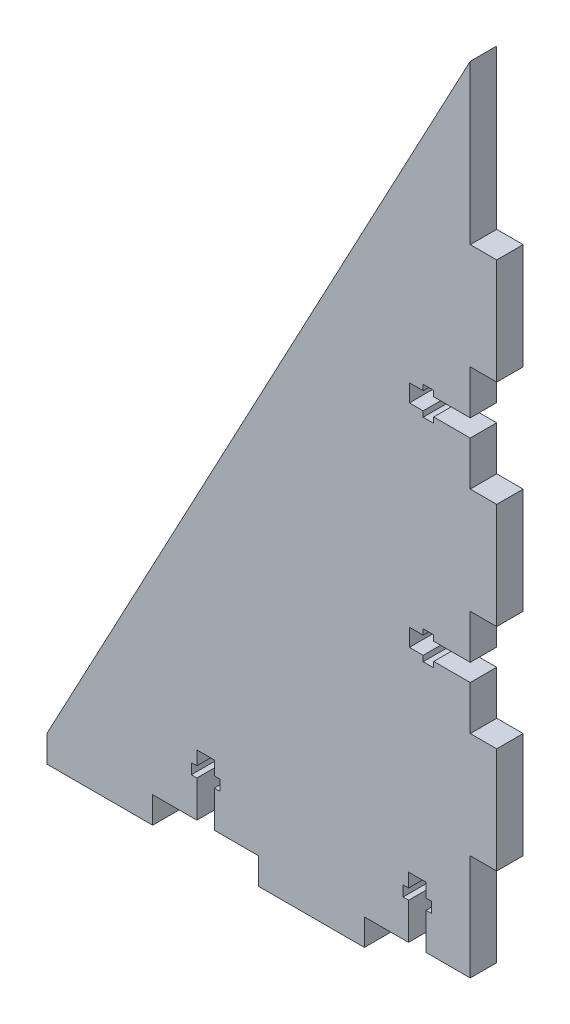
SolidWorks part; units mm, degrees
ref_plane "Front Plane" through (0, 0, 0) normal (0, 0, 1) x (1, 0, 0)
ref_plane "Top Plane" through (0, 0, 0) normal (0, 1, 0) x (1, 0, 0)
ref_plane "Right Plane" through (0, 0, 0) normal (1, 0, 0) x (0, 0, -1)
sketch "Sketch1" plane through (0, 0, 0) normal (0, 0, 1) x (1, 0, 0)
  line L0 (49.1901, 285.75) -> (49.1901, 95.25)
  line L1 (49.1901, 340.0125) -> (49.1901, 289.2125) construction
  line L2 (49.1901, 95.25) -> (-52.4099, 95.25)
  line L3 (-52.4099, 95.25) -> (49.1901, 285.75)
  dimension "D1" = 101.6
  dimension "D2" = 190.5
extrude "Boss-Extrude1" add sketch "Sketch1" along normal mid plane 6.35
sketch "Sketch2" plane through (49.1901, 0, 0) normal (1, 0, 0) x (0, 0, -1)
  line L0 (3.175, 95.25) -> (3.175, 285.75) construction
  line L1 (3.175, 120.65) -> (-3.175, 120.65)
  line L2 (3.175, 120.65) -> (3.175, 146.05)
  line L3 (3.175, 146.05) -> (-3.175, 146.05)
  line L4 (-3.175, 120.65) -> (-3.175, 146.05)
  line L5 (-3.175, 95.25) -> (-3.175, 285.75) construction
  dimension "D1" = 25.4
  dimension "D2" = 25.4
extrude "Boss-Extrude2" add sketch "Sketch2" along normal blind 6.35
pattern_linear "LPattern1" count 3 spacing 50.8 along (0, 1, 0) of "Boss-Extrude2"
sketch "Sketch3" plane through (0, 95.25, 0) normal (0, -1, 0) x (1, 0, 0)
  line L0 (-52.4099, 3.175) -> (49.1901, 3.175) construction
  line L1 (23.7901, 3.175) -> (-1.6099, 3.175)
  line L2 (23.7901, 3.175) -> (23.7901, -3.175)
  line L3 (23.7901, -3.175) -> (-1.6099, -3.175)
  line L4 (-1.6099, 3.175) -> (-1.6099, -3.175)
  line L5 (-52.4099, -3.175) -> (49.1901, -3.175) construction
  dimension "D1" = 25.4
  dimension "D2" = 25.4
extrude "Boss-Extrude3" add sketch "Sketch3" along normal blind 6.35
pattern_linear "LPattern2" count 2 spacing 50.8 along (-1, 0, 0) of "Boss-Extrude3"
sketch "Sketch4" plane through (0, 0, 3.175) normal (0, 0, 1) x (1, 0, 0)
  line L0 (49.1901, 209.55) -> (33.1373, 209.55) construction
  line L1 (49.1901, 196.85) -> (49.1901, 222.25) construction
  line L2 (49.1901, 158.75) -> (29.9838, 158.75) construction
  line L3 (49.1901, 146.05) -> (49.1901, 171.45) construction
  line L4 (36.4901, 95.25) -> (36.4901, 105.3284) construction
  line L5 (23.7901, 95.25) -> (49.1901, 95.25) construction
  line L6 (49.1901, 107.95) -> (40.5585, 107.95) construction
  line L7 (49.1901, 95.25) -> (49.1901, 120.65) construction
  line L8 (-14.3099, 95.25) -> (-14.3099, 106.6187) construction
  line L10 (-27.0099, 95.25) -> (-1.6099, 95.25) construction
  line B0 (49.1901, 156.6545) -> (49.1901, 160.8455)
  line B1 (37.8871, 160.8455) -> (37.8871, 162.179)
  line B2 (37.8871, 162.179) -> (40.4271, 162.179)
  line B3 (40.4271, 162.179) -> (40.4271, 160.8455)
  line B4 (40.4271, 160.8455) -> (49.1901, 160.8455)
  line B5 (37.8871, 160.8455) -> (34.5851, 160.8455)
  line B6 (34.5851, 160.8455) -> (34.5851, 156.6545)
  line B7 (37.8871, 156.6545) -> (34.5851, 156.6545)
  line B8 (40.4271, 156.6545) -> (49.1901, 156.6545)
  line B9 (40.4271, 155.321) -> (40.4271, 156.6545)
  line B10 (37.8871, 155.321) -> (40.4271, 155.321)
  line B11 (37.8871, 156.6545) -> (37.8871, 155.321)
  line B12 (-16.4054, 95.25) -> (-12.2144, 95.25)
  line B13 (-12.2144, 106.553) -> (-10.8809, 106.553)
  line B14 (-10.8809, 106.553) -> (-10.8809, 104.013)
  line B15 (-10.8809, 104.013) -> (-12.2144, 104.013)
  line B16 (-12.2144, 104.013) -> (-12.2144, 95.25)
  line B17 (-12.2144, 106.553) -> (-12.2144, 109.855)
  line B18 (-12.2144, 109.855) -> (-16.4054, 109.855)
  line B19 (-16.4054, 106.553) -> (-16.4054, 109.855)
  line B20 (-16.4054, 104.013) -> (-16.4054, 95.25)
  line B21 (-17.7389, 104.013) -> (-16.4054, 104.013)
  line B22 (-17.7389, 106.553) -> (-17.7389, 104.013)
  line B23 (-16.4054, 106.553) -> (-17.7389, 106.553)
  line B24 (49.1901, 207.4545) -> (49.1901, 211.6455)
  line B25 (37.8871, 211.6455) -> (37.8871, 212.979)
  line B26 (37.8871, 212.979) -> (40.4271, 212.979)
  line B27 (40.4271, 212.979) -> (40.4271, 211.6455)
  line B28 (40.4271, 211.6455) -> (49.1901, 211.6455)
  line B29 (37.8871, 211.6455) -> (34.5851, 211.6455)
  line B30 (34.5851, 211.6455) -> (34.5851, 207.4545)
  line B31 (37.8871, 207.4545) -> (34.5851, 207.4545)
  line B32 (40.4271, 207.4545) -> (49.1901, 207.4545)
  line B33 (40.4271, 206.121) -> (40.4271, 207.4545)
  line B34 (37.8871, 206.121) -> (40.4271, 206.121)
  line B35 (37.8871, 207.4545) -> (37.8871, 206.121)
  line B36 (34.3946, 95.25) -> (38.5856, 95.25)
  line B37 (38.5856, 106.553) -> (39.9191, 106.553)
  line B38 (39.9191, 106.553) -> (39.9191, 104.013)
  line B39 (39.9191, 104.013) -> (38.5856, 104.013)
  line B40 (38.5856, 104.013) -> (38.5856, 95.25)
  line B41 (38.5856, 106.553) -> (38.5856, 109.855)
  line B42 (38.5856, 109.855) -> (34.3946, 109.855)
  line B43 (34.3946, 106.553) -> (34.3946, 109.855)
  line B44 (34.3946, 104.013) -> (34.3946, 95.25)
  line B45 (33.0611, 104.013) -> (34.3946, 104.013)
  line B46 (33.0611, 106.553) -> (33.0611, 104.013)
  line B47 (34.3946, 106.553) -> (33.0611, 106.553)
sketch_block_instance "TSlot-1"
sketch_block "Block1" parameters "D1"=3.302, "D2"=2.54, "D3"=3.175, "D4"=8.763, "D5"=1.3462
sketch_block_instance "Block1-1"
sketch_block_instance "Block1-4"
sketch_block_instance "Block1-7"
extrude "Cut-Extrude1" cut sketch "Sketch4" against normal through all
